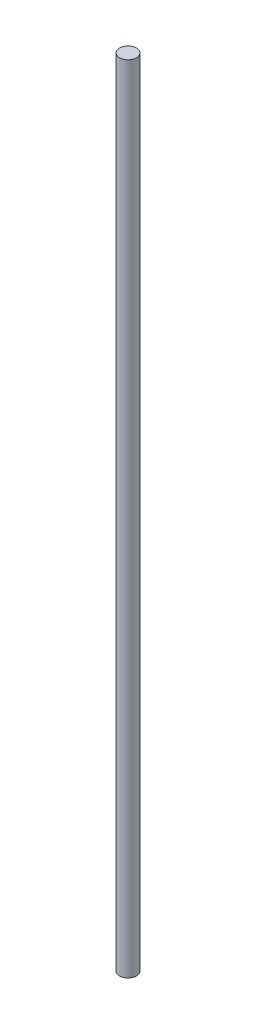
SolidWorks part; units mm, degrees
ref_plane "Front Plane" through (0, 0, 0) normal (0, 0, 1) x (1, 0, 0)
ref_plane "Top Plane" through (0, 0, 0) normal (0, 1, 0) x (1, 0, 0)
ref_plane "Right Plane" through (0, 0, 0) normal (1, 0, 0) x (0, 0, -1)
sketch "Sketch1" plane through (0, 0, 0) normal (0, 1, 0) x (1, 0, 0)
  circle A0 centre (0, 0) radius 6.35
  dimension "D1" = 12.7
extrude "Boss-Extrude1" add sketch "Sketch1" along normal blind 596.9
